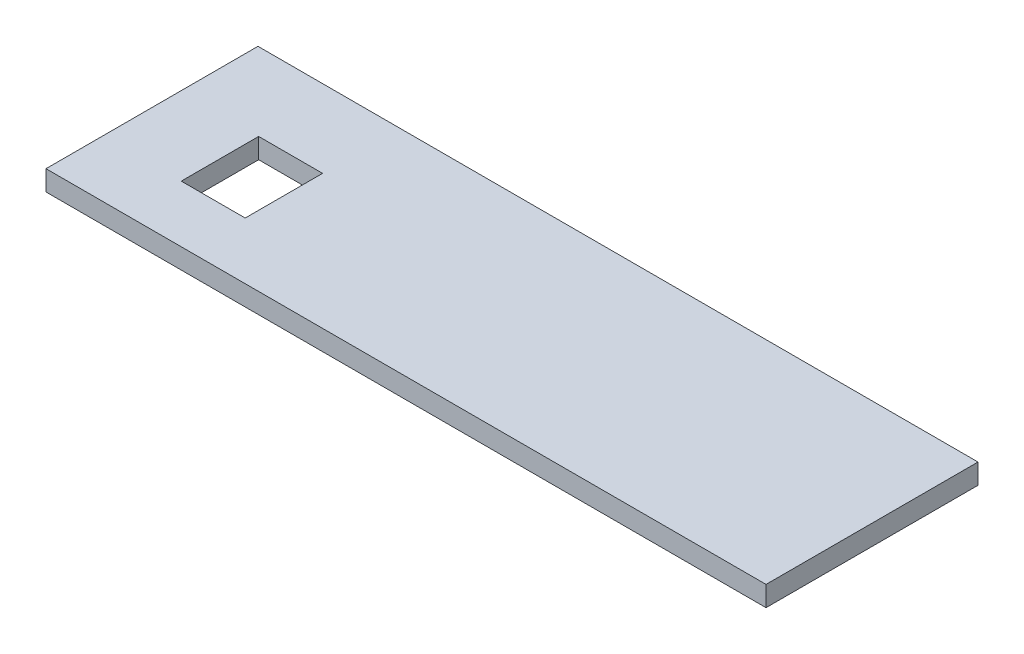
SolidWorks part; units mm, degrees
ref_plane "Спереди" through (0, 0, 0) normal (0, 0, 1) x (1, 0, 0)
ref_plane "Сверху" through (0, 0, 0) normal (0, 1, 0) x (1, 0, 0)
ref_plane "Справа" through (0, 0, 0) normal (1, 0, 0) x (0, 0, -1)
other "Configuration Table"
sketch "Эскиз1" plane through (0, 0, 0) normal (0, 1, 0) x (1, 0, 0)
  line L1 (0, -31.5) -> (107, -31.5)
  line L2 (0, -31.5) -> (0, 0)
  line L3 (0, 0) -> (107, 0)
  line L4 (107, -31.5) -> (107, 0)
  line L5 (11.65, -23.05) -> (21.15, -23.05)
  line L6 (11.65, -23.05) -> (11.65, -11.55)
  line L7 (11.65, -11.55) -> (21.15, -11.55)
  line L8 (21.15, -23.05) -> (21.15, -11.55)
extrude "Бобышка-Вытянуть1" add sketch "Эскиз1" along normal blind 3
